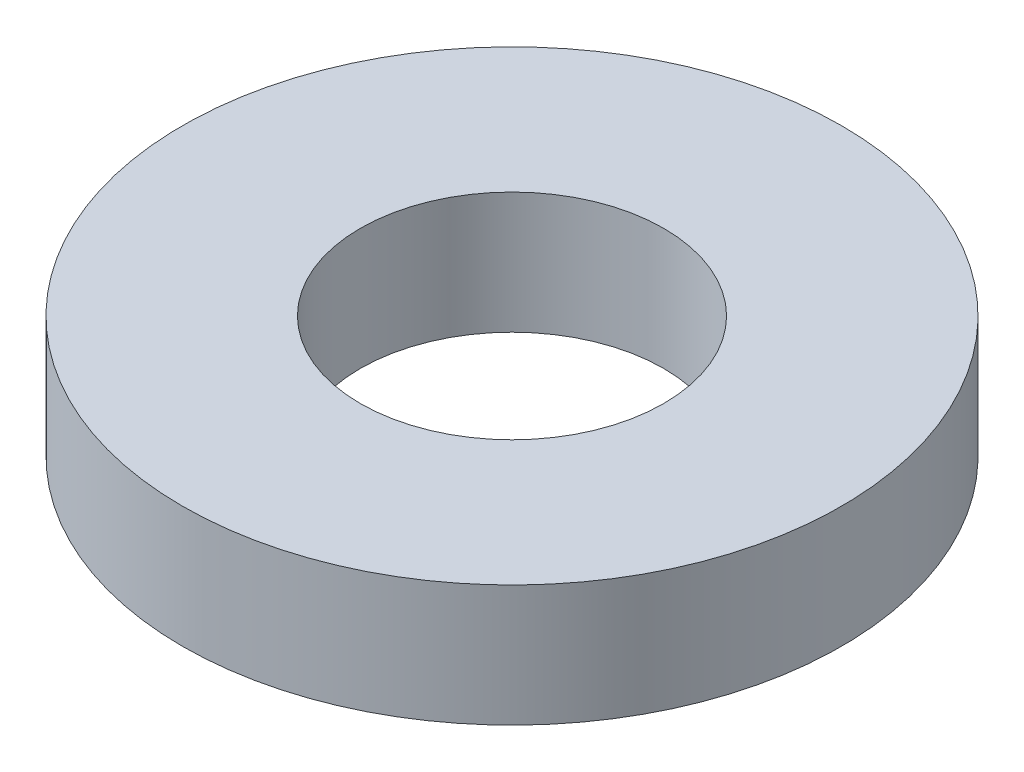
SolidWorks part; units mm, degrees
ref_plane "Front Plane" through (0, 0, 0) normal (0, 0, 1) x (1, 0, 0)
ref_plane "Top Plane" through (0, 0, 0) normal (0, 1, 0) x (1, 0, 0)
ref_plane "Right Plane" through (0, 0, 0) normal (1, 0, 0) x (0, 0, -1)
sketch "Sketch1" plane through (0, 0, 0) normal (0, 1, 0) x (1, 0, 0)
  circle A0 centre (0, 0) radius 6.8961
  circle A1 centre (0, 0) radius 3.175
  dimension "D1" = 13.7922
  dimension "D2" = 6.35
extrude "Boss-Extrude1" add sketch "Sketch1" along normal blind 2.54
